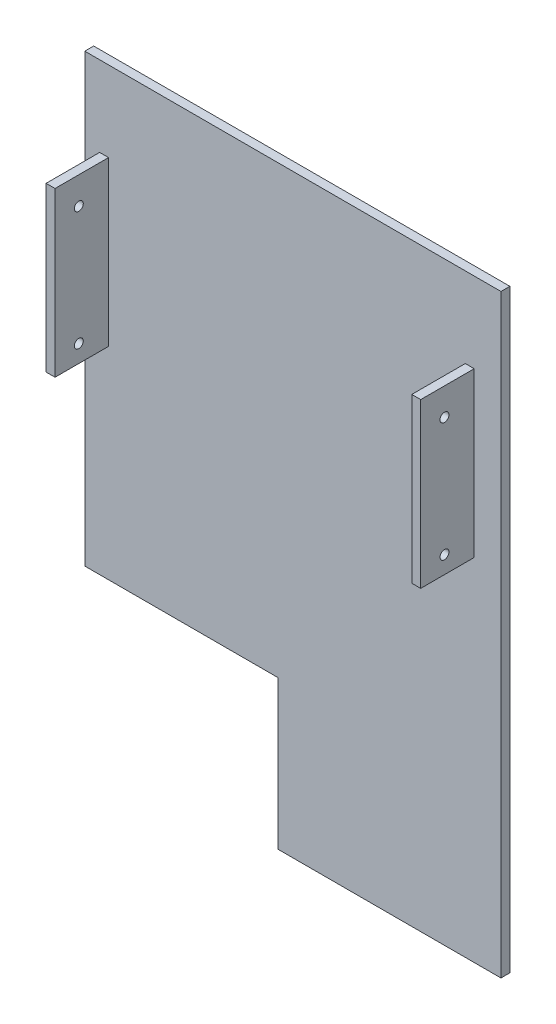
SolidWorks part; units mm, degrees
ref_plane "前视基准面" through (0, 0, 0) normal (0, 0, 1) x (1, 0, 0)
ref_plane "上视基准面" through (0, 0, 0) normal (0, 1, 0) x (1, 0, 0)
ref_plane "右视基准面" through (0, 0, 0) normal (1, 0, 0) x (0, 0, -1)
sketch "草图1" plane through (0, 0, 0) normal (0, 0, 1) x (1, 0, 0)
  line L1 (0, 0) -> (140, 0)
  line L2 (0, 0) -> (0, -200)
  line L3 (0, -200) -> (140, -200)
  line L4 (140, 0) -> (140, -200)
  dimension "D1" = 140
  dimension "D2" = 200
extrude "凸台-拉伸1" add sketch "草图1" along normal blind 3
sketch "草图2" plane through (0, 0, 0) normal (0, 0, -1) x (-1, 0, 0)
  line L0 (0, -200) -> (-140, -200) construction
  line L1 (-65, -200) -> (0, -200)
  line L2 (-65, -200) -> (-65, -150)
  line L3 (-65, -150) -> (0, -150)
  line L4 (0, -200) -> (0, -150)
  line L5 (0, 0) -> (0, -200) construction
  dimension "D1" = 65
  dimension "D2" = 50
extrude "切除-拉伸1" cut sketch "草图2" against normal blind 10
sketch "草图4" plane through (0, 0, 3) normal (0, 0, 1) x (1, 0, 0)
  line L1 (5, -27) -> (8, -27)
  line L3 (5, -82) -> (8, -82)
  line L4 (8, -27) -> (8, -82)
  line L5 (8, -116.1645) -> (8, -6.1645) construction
  line L6 (140, 0) -> (0, 0) construction
  line L8 (8, -27) -> (5, -27)
  line L9 (8, -27) -> (8, -82)
  line L10 (8, -82) -> (5, -82)
  line L11 (5, -27) -> (5, -82)
  dimension "D1" = 27
  dimension "D3" = 3
extrude "凸台-拉伸4" add sketch "草图4" along normal blind 18 contours L1 L11 L3 L4
sketch "草图5" plane through (5, 0, 0) normal (-1, 0, 0) x (0, 0, 1)
  circle A0 centre (13, -76.1645) radius 1.5 construction
  circle A1 centre (13, -76.1645) radius 1.5
  circle A2 centre (13, -36.1645) radius 1.5 construction
  circle A3 centre (13, -36.1645) radius 1.5
extrude "切除-拉伸2" cut sketch "草图5" against normal up to next
sketch "草图6" plane through (128, 0, 0) normal (1, 0, 0) x (0, 0, -1)
  line L4 (-3, -82) -> (-3, -27)
  line L5 (-21, -82) -> (-3, -82)
  line L6 (-21, -27) -> (-21, -82)
  line L7 (-3, -27) -> (-21, -27)
  line L8 (-3, -82) -> (-3, -27)
  line L9 (-21, -82) -> (-3, -82)
  line L10 (-21, -27) -> (-21, -82)
  line L11 (-3, -27) -> (-21, -27)
  circle A0 centre (-13, -76.1645) radius 1.5 construction
  circle A1 centre (-13, -76.1645) radius 1.5
  circle A2 centre (-13, -36.1645) radius 1.5 construction
  circle A3 centre (-13, -36.1645) radius 1.5
  dimension "D1" = 0
extrude "凸台-拉伸6" add sketch "草图6" along normal blind 3
